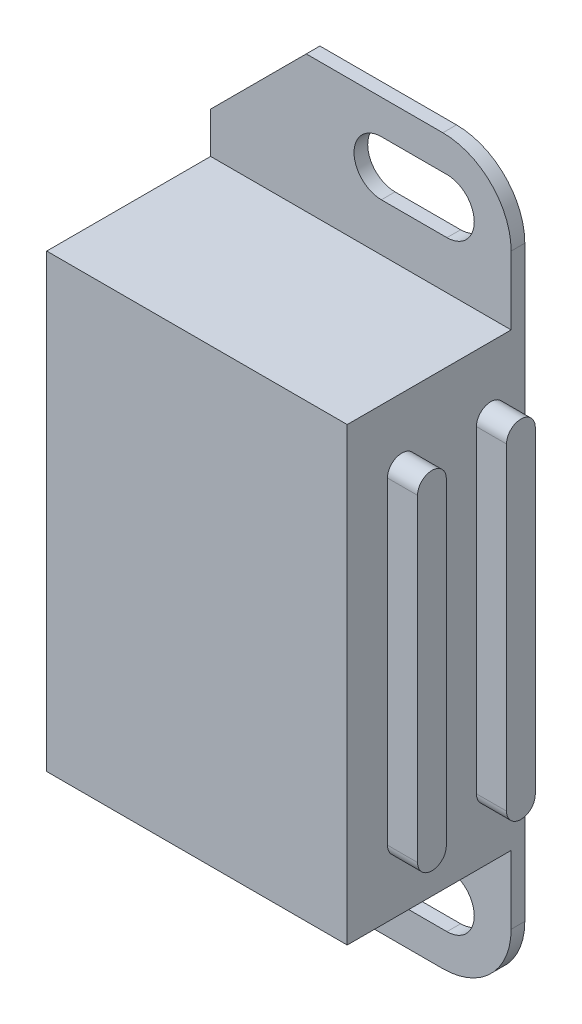
SolidWorks part; units mm, degrees
ref_plane "前视基准面" through (0, 0, 0) normal (0, 0, 1) x (1, 0, 0)
ref_plane "上视基准面" through (0, 0, 0) normal (0, 1, 0) x (1, 0, 0)
ref_plane "右视基准面" through (0, 0, 0) normal (1, 0, 0) x (0, 0, -1)
sketch "草图1" plane through (0, 0, 0) normal (0, 0, 1) x (1, 0, 0)
  line L1 (-11, -26.5) -> (11, -26.5)
  line L2 (-11, -26.5) -> (-11, 26.5)
  line L3 (-11, 26.5) -> (11, 26.5)
  line L4 (11, -26.5) -> (11, 26.5)
  line L5 (-11, -26.5) -> (11, 26.5) construction
  line L6 (-11, 26.5) -> (11, -26.5) construction
  point P0 (0, 0)
  dimension "D1" = 22
  dimension "D2" = 53
extrude "凸台-拉伸1" add sketch "草图1" along normal blind 1
sketch "草图2" plane through (0, 0, 1) normal (0, 0, 1) x (1, 0, 0)
  line L0 (1.5, 22) -> (6.3, 22) construction
  line L1 (1.5, 24) -> (6.3, 24)
  line L2 (1.5, 20) -> (6.3, 20)
  line L3 (11, 26.5) -> (-11, 26.5) construction
  line L4 (0, 0) -> (-11, 0) construction
  line L5 (-11, 26.5) -> (-11, -26.5) construction
  arc A0 (1.5, 24) -> (1.5, 20) centre (1.5, 22) ccw
  arc A1 (6.3, 20) -> (6.3, 24) centre (6.3, 22) ccw
  point P2 (3.9, 22)
  point P7 (0, 26.5)
  dimension "D2" = 2
  dimension "D4" = 12.5
  dimension "D1" = 4.8
  dimension "D3" = 4.5
extrude "切除-拉伸1" cut sketch "草图2" against normal through all
mirror "镜向1" about plane through (0, 0, 0) normal (0, 1, 0) of "切除-拉伸1"
sketch "草图3" plane through (0, 0, 1) normal (0, 0, 1) x (1, 0, 0)
  line L0 (11, -26.5) -> (11, 26.5) construction
  line L1 (-11, -16.5) -> (11, -16.5)
  line L2 (-11, -16.5) -> (-11, 16.5)
  line L3 (-11, 16.5) -> (11, 16.5)
  line L4 (11, -16.5) -> (11, 16.5)
  line L5 (-11, -16.5) -> (11, 16.5) construction
  line L6 (-11, 16.5) -> (11, -16.5) construction
  point P0 (0, 0)
  dimension "D1" = 33
extrude "凸台-拉伸2" add sketch "草图3" along normal blind 12
sketch "草图4" plane through (11, 0, 0) normal (1, 0, 0) x (0, 0, -1)
  line L0 (-9, -11.6386) -> (-9, 11.6386) construction
  line L1 (-10.0541, -11.6386) -> (-10.0541, 11.6386)
  line L2 (-7.9459, -11.6386) -> (-7.9459, 11.6386)
  line L3 (-13, -16.5) -> (-13, 16.5) construction
  line L4 (-5.7432, 16.5) -> (-5.7432, -7.1789) construction
  line L5 (-13, 16.5) -> (-1, 16.5) construction
  line L6 (-2.4864, -11.6386) -> (-2.4864, 11.6386) construction
  line L7 (-1.4323, -11.6386) -> (-1.4323, 11.6386)
  line L8 (-3.5405, -11.6386) -> (-3.5405, 11.6386)
  arc A0 (-10.0541, -11.6386) -> (-7.9459, -11.6386) centre (-9, -11.6386) ccw
  arc A1 (-7.9459, 11.6386) -> (-10.0541, 11.6386) centre (-9, 11.6386) ccw
  arc A2 (-1.4323, -11.6386) -> (-3.5405, -11.6386) centre (-2.4864, -11.6386) cw
  arc A3 (-3.5405, 11.6386) -> (-1.4323, 11.6386) centre (-2.4864, 11.6386) cw
  point P2 (-9, 0)
  point P15 (-2.4864, 0)
  dimension "D1" = 4
extrude "凸台-拉伸3" add sketch "草图4" along normal blind 2.2
chamfer "倒角1" distance 7 angle 45 2 edges at (-11, -26.5, 0.5) (-11, 26.5, 0.5)
fillet "圆角1" radius 5 2 edges at (11, -26.5, 0.5) (11, 26.5, 0.5)
